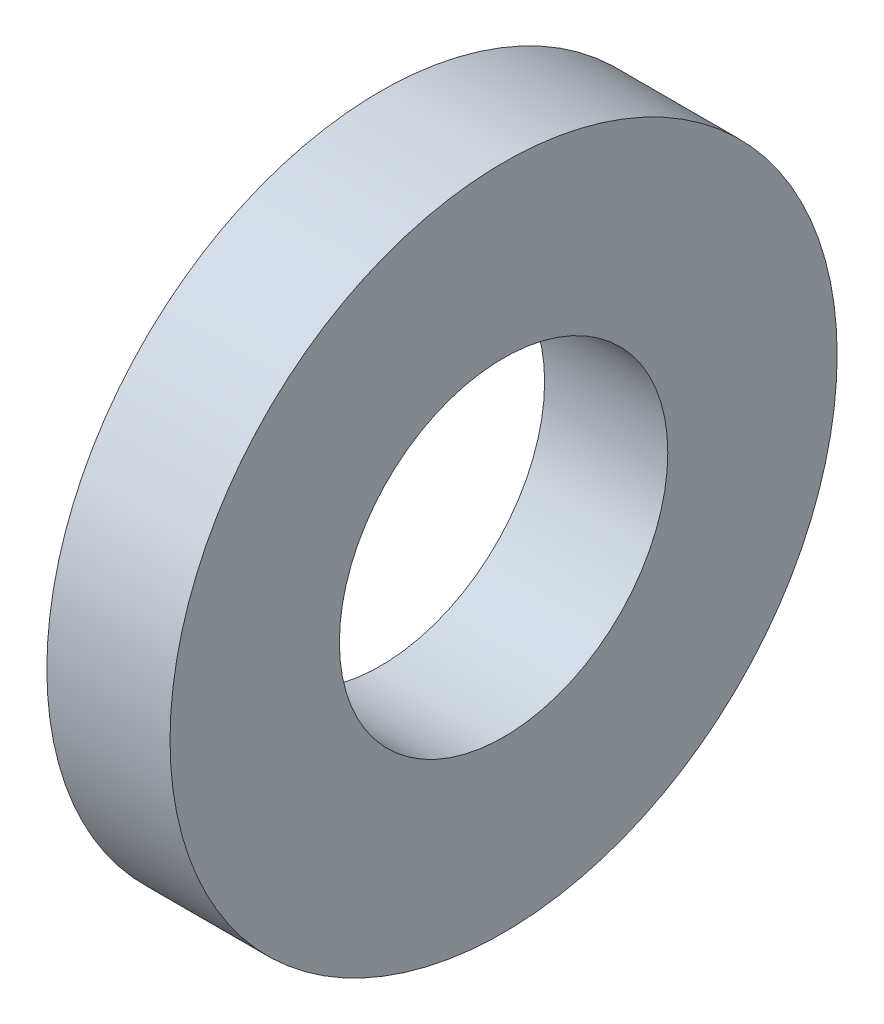
SolidWorks part; units mm, degrees
ref_plane "Front" through (0, 0, 0) normal (0, 0, 1) x (1, 0, 0)
ref_plane "Top" through (0, 0, 0) normal (0, 1, 0) x (1, 0, 0)
ref_plane "Right" through (0, 0, 0) normal (1, 0, 0) x (0, 0, -1)
sketch "Sketch1" plane through (0, 0, 0) normal (1, 0, 0) x (0, 0, -1)
  circle A0 centre (0, 0) radius 3.2
  circle A1 centre (0, 0) radius 6.5
extrude "Boss-Extrude1" add sketch "Sketch1" along normal blind 2.4
